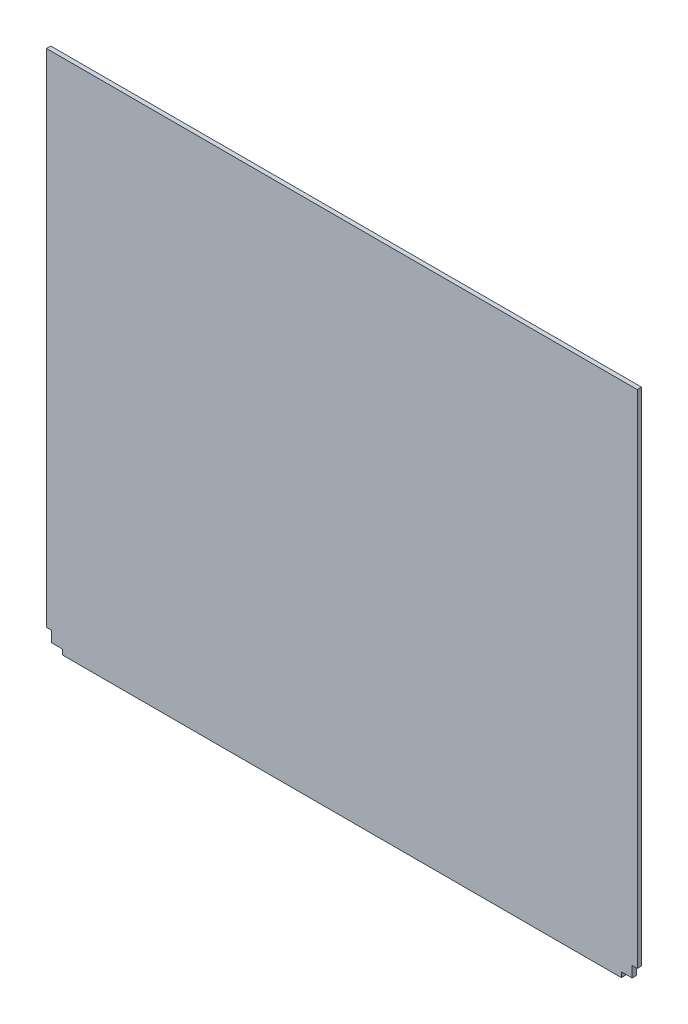
SolidWorks part; units mm, degrees
material "PE High Density"
ref_plane "Front Plane" through (0, 0, 0) normal (0, 0, 1) x (1, 0, 0)
ref_plane "Top Plane" through (0, 0, 0) normal (0, 1, 0) x (1, 0, 0)
ref_plane "Right Plane" through (0, 0, 0) normal (1, 0, 0) x (0, 0, -1)
sketch "Sketch1" plane through (0, 0, 0) normal (0, 0, 1) x (1, 0, 0)
  line L4 (16.1251, -7.62) -> (16.1251, 0)
  line L5 (0, 16.1251) -> (-7.62, 16.1251)
  line L8 (-7.62, 762.508) -> (871.982, 762.508)
  line L9 (871.982, 762.508) -> (871.982, 16.1251)
  line L10 (848.2369, -7.62) -> (16.1251, -7.62)
  line L11 (-7.62, 16.1251) -> (-7.62, 762.508)
  line L12 (0, 16.1251) -> (0, 0)
  line L13 (0, 0) -> (16.1251, 0)
  line L14 (432.181, -7.62) -> (432.181, 762.508) construction
  line L15 (848.2369, -7.62) -> (848.2369, 0)
  line L16 (864.362, 0) -> (848.2369, 0)
  line L17 (864.362, 16.1251) -> (864.362, 0)
  line L18 (864.362, 16.1251) -> (871.982, 16.1251)
  dimension "D1" = 770.128
  dimension "D2" = 7.62
  dimension "D4" = 879.602
  dimension "D5" = 16.1251
extrude "Boss-Extrude1" add sketch "Sketch1" along normal blind 6.35
